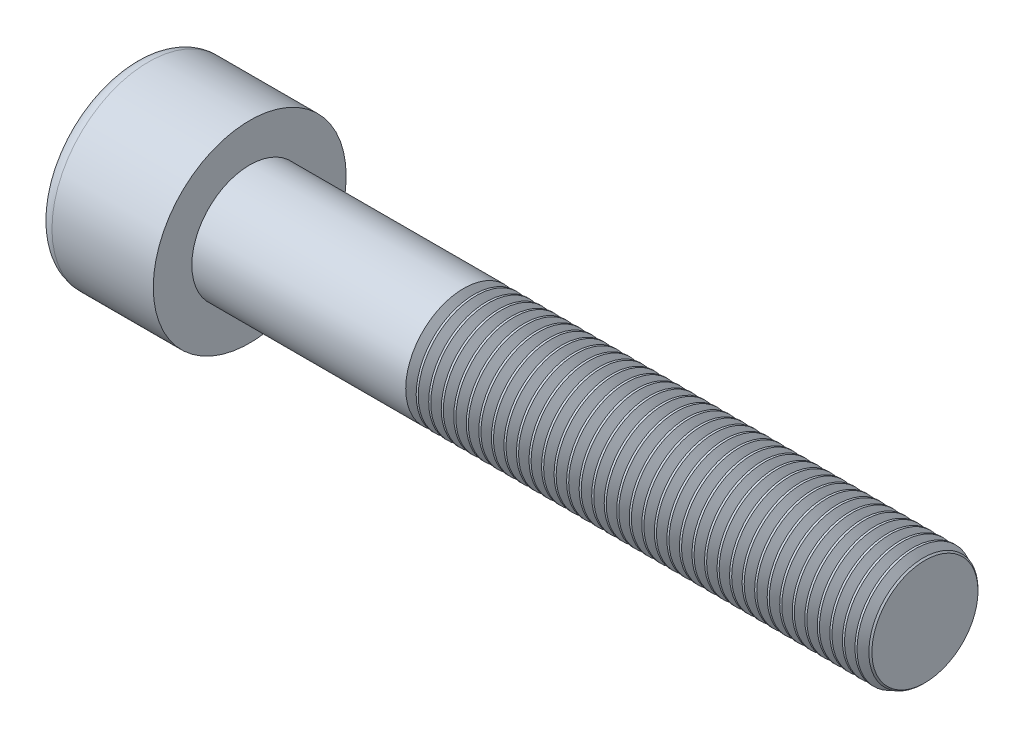
SolidWorks part; units mm, degrees
ref_plane "Front" through (0, 0, 0) normal (0, 0, 1) x (1, 0, 0)
ref_plane "Top" through (0, 0, 0) normal (0, 1, 0) x (1, 0, 0)
ref_plane "Right" through (0, 0, 0) normal (1, 0, 0) x (0, 0, -1)
sketch "Sketch1" plane through (0, 0, 0) normal (1, 0, 0) x (0, 0, -1)
  circle A0 centre (0, 0) radius 5
  dimension "dk" = 10
extrude "BaseHead" add sketch "Sketch1" along normal blind 6
sketch "Sketch2" plane through (6, 0, 0) normal (1, 0, 0) x (0, 0, -1)
  circle A0 centre (0, 0) radius 3
  dimension "d" = 6
extrude "BaseBody" add sketch "Sketch2" along normal blind 35
cosmetic thread "ThreadCosmetic1" [suppressed] parameters "b"=24, "D2"=4.917
sketch "Sketch3" plane through (0, 0, 0) normal (1, 0, 0) x (0, 0, -1)
  line L1 (2.8868, 0) -> (1.4434, 2.5)
  line L2 (1.4434, 2.5) -> (-1.4434, 2.5)
  line L3 (-1.4434, 2.5) -> (-2.8868, 0)
  line L4 (-2.8868, 0) -> (-1.4434, -2.5)
  line L5 (-1.4434, -2.5) -> (1.4434, -2.5)
  line L6 (1.4434, -2.5) -> (2.8868, 0)
  circle A0 centre (0, 0) radius 2.5 construction
  dimension "s" = 5
  dimension "e" = 5.7735
extrude "HexagonSocket" cut sketch "Sketch3" along normal blind 3
sketch "Sketch4" plane through (-4.1961, 0.75, 0) normal (0, 0, 1) x (-1, 0, 0)
  line L0 (-7.1961, 3.25) -> (-8.6395, 0.75)
  line L2 (-8.6395, 0.75) -> (-7.1961, 0.75)
  line L3 (-7.1961, 0.75) -> (-7.1961, 3.25)
  line L4 (-5.0351, 0.75) -> (0.839, 0.75) construction
  line L5 (-45.1961, 0.75) -> (-10.1961, 0.75) construction
  line L6 (-10.1961, 0.75) -> (-4.1961, 0.75) construction
  dimension "m" = 60
revolve "Cut-Revolve1" cut sketch "Sketch4" angle 360 about L4
fillet "HeadFillet" [suppressed] radius 0.25
fillet "TopFillet" radius 0.75 1 edges at (0, 0, -5)
chamfer "Chamfer1" distance 0.25 angle 45 1 edges at (41, 0, -3)
sketch "Sketch5" plane through (0, 0, 0) normal (0, 0, 1) x (1, 0, 0)
  line L0 (40.75, 2.531) -> (41.0208, 3)
  line L1 (41.0208, 3) -> (41.0208, 3.5415)
  line L2 (41.0208, 3.5415) -> (40.4793, 3.5415)
  line L3 (40.4793, 3.5415) -> (40.4793, 3)
  line L4 (40.4793, 3) -> (40.75, 2.531)
  line L5 (0, 0) -> (7.8886, 0) construction
  line L6 (40.75, -3) -> (40.75, 3) construction
  dimension "D1" = 6
  dimension "D2" = 0.5415
revolve "Cut-Revolve10" cut sketch "Sketch5" angle 360 about L5
pattern_linear "LPattern10" count 37 spacing 0.6498 along (-1, 0, 0) of "Cut-Revolve10"
equation "\"r1@TopFillet\" = \"d@Sketch2\" / 8"
equation "\"D1@Chamfer1\" = \"r@HeadFillet\""
equation "\"D1@Sketch5\" = \"d@Sketch2\""
equation "\"D2@Sketch5\" =  ( \"d@Sketch2\" - \"D2@ThreadCosmetic1\" )  / 2"
equation "\"D3@LPattern10\" = \"D2@Sketch5\" * 1.2"
equation "\"D1@LPattern10\" = \"b@ThreadCosmetic1\" / \"D3@LPattern10\""
